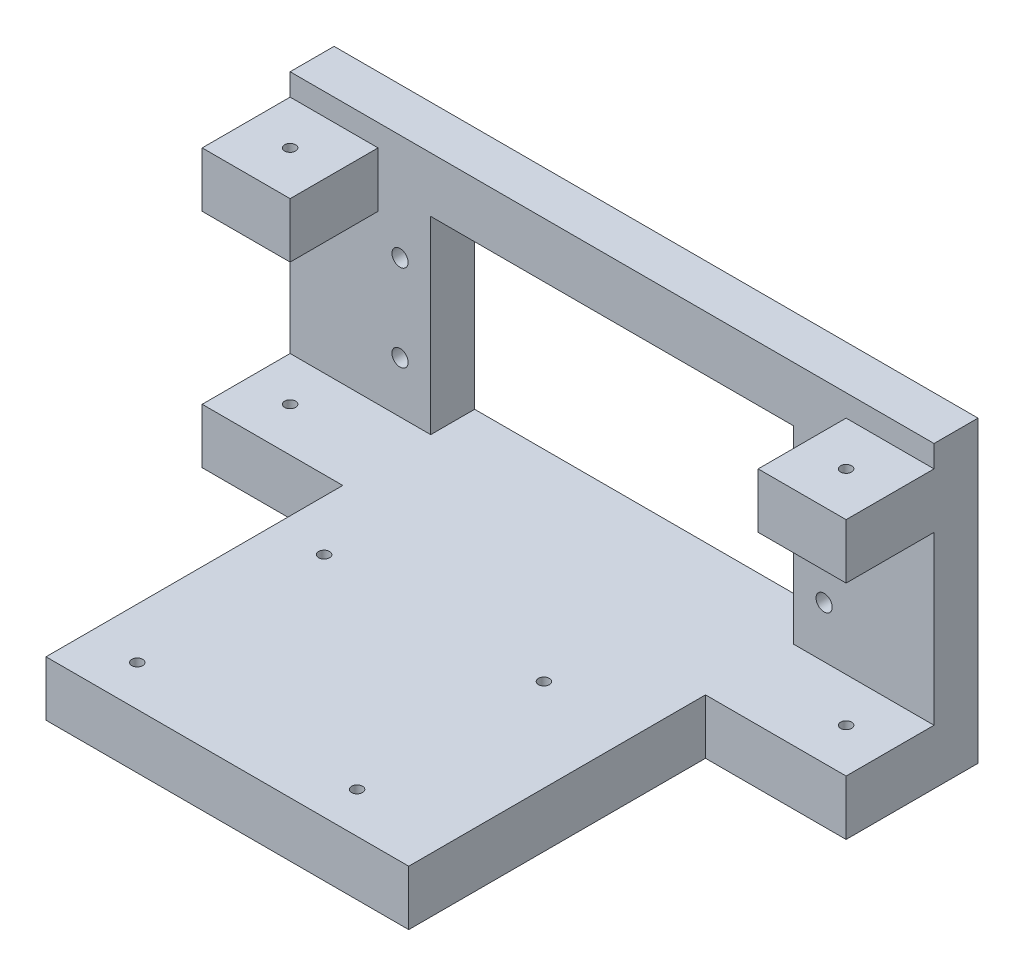
SolidWorks part; units mm, degrees
ref_plane "Front Plane" through (0, 0, 0) normal (0, 0, 1) x (1, 0, 0)
ref_plane "Top Plane" through (0, 0, 0) normal (0, 1, 0) x (1, 0, 0)
ref_plane "Right Plane" through (0, 0, 0) normal (1, 0, 0) x (0, 0, -1)
sketch "Sketch1" plane through (0, 0, 0) normal (0, 0, 1) x (1, 0, 0)
  line L1 (0, 0) -> (54.61, 0)
  line L2 (0, 0) -> (0, 47.244)
  line L3 (0, 47.244) -> (54.61, 47.244)
  line L4 (54.61, 0) -> (54.61, 47.244)
  line L5 (6.35, 12.7) -> (48.26, 12.7)
  line L6 (6.35, 12.7) -> (6.35, 34.544)
  line L7 (6.35, 34.544) -> (48.26, 34.544)
  line L8 (48.26, 12.7) -> (48.26, 34.544)
  dimension "D1" = 41.91
  dimension "D2" = 21.844
  dimension "D3" = 6.35
  dimension "D4" = 6.35
  dimension "D5" = 12.7
  dimension "D6" = 12.7
extrude "Boss-Extrude1" add sketch "Sketch1" along normal blind 5.08
sketch "Sketch2" plane through (0, 0, 5.08) normal (0, 0, 1) x (1, 0, 0)
  line L0 (0, 23.622) -> (54.61, 23.622) construction
  line L1 (2.8054, 28.622) -> (51.8046, 28.622) construction
  line L2 (2.8054, 28.622) -> (2.8054, 18.622) construction
  line L3 (2.8054, 18.622) -> (51.8046, 18.622) construction
  line L4 (51.8046, 28.622) -> (51.8046, 18.622) construction
  line L5 (0, 47.244) -> (0, 0) construction
  line L6 (54.61, 0) -> (54.61, 47.244) construction
  line L7 (2.8054, 23.622) -> (51.8046, 23.622) construction
  line L8 (27.305, 28.622) -> (27.305, 18.622) construction
  line L9 (27.305, 47.244) -> (27.305, 0) construction
  line L10 (54.61, 47.244) -> (0, 47.244) construction
  line L11 (0, 0) -> (54.61, 0) construction
  line L12 (25.1752, 42.164) -> (29.4348, 42.164) construction
  line L13 (29.4348, 42.164) -> (29.4348, 5.08) construction
  line L14 (29.4348, 5.08) -> (25.1752, 5.08) construction
  line L15 (25.1752, 5.08) -> (25.1752, 42.164) construction
  line L16 (48.26, 34.544) -> (6.35, 34.544) construction
  line L17 (6.35, 12.7) -> (48.26, 12.7) construction
  circle A0 centre (2.8054, 28.622) radius 0.936
  circle A1 centre (2.8054, 18.622) radius 0.936
  circle A2 centre (51.8046, 28.622) radius 0.936
  circle A3 centre (51.8046, 18.622) radius 0.936
  circle A4 centre (25.1752, 5.08) radius 0.635 construction
  circle A5 centre (29.4348, 5.08) radius 0.635 construction
  circle A6 centre (29.4348, 42.164) radius 0.635 construction
  circle A7 centre (25.1752, 42.164) radius 0.635 construction
  point P16 (2.8054, 27.686)
  point P17 (2.8054, 19.558)
  dimension "D2" = 8.128
  dimension "D4" = 1.872
  dimension "D5" = 1.27
  dimension "D1" = 10
  dimension "D3" = 48.9991
  dimension "D6" = 4.2596
  dimension "D7" = 2.1298
  dimension "D8" = 7.62
  dimension "D9" = 7.62
  dimension "D10" = 37.084
extrude "Cut-Extrude1" cut sketch "Sketch2" against normal through all
sketch "Sketch10" plane through (0, 0, 5.08) normal (0, 0, 1) x (1, 0, 0)
  line L0 (0, 47.244) -> (0, 80.7756)
  line L1 (0, 80.7756) -> (-31.1018, 80.7756)
  line L2 (0, 47.244) -> (0, 0)
  line L3 (-31.1018, 80.7756) -> (-31.1018, -10.4159)
  line L4 (-31.1018, -10.4159) -> (0, -10.4159)
  line L5 (0, 23.622) -> (54.61, 23.622) construction
  line L6 (54.61, 0) -> (54.61, 47.244) construction
  line L7 (54.61, 23.622) -> (62.23, 23.622) construction
  line L8 (62.23, 23.622) -> (66.4896, 23.622)
  line L9 (-13.8825, 79.8399) -> (-11.43, 79.8399)
  line L10 (-13.8825, 79.8399) -> (-13.8825, 3.6399)
  line L11 (-13.8825, 3.6399) -> (-11.43, 3.6399)
  line L12 (-11.43, 79.8399) -> (-11.43, 3.6399)
  line L13 (0, -10.4159) -> (0, 47.244)
  line L14 (69.0296, 23.622) -> (66.4896, 23.622) construction
  line L15 (0, 47.244) -> (0, 0) construction
  line L16 (64.3598, 25.7518) -> (64.3598, 21.4922) construction
  line L17 (54.61, 33.3718) -> (69.0296, 33.3718)
  line L18 (54.61, 33.3718) -> (54.61, 13.8722)
  line L19 (54.61, 13.8722) -> (69.0296, 13.8722)
  line L20 (69.0296, 33.3718) -> (69.0296, 13.8722)
  line L21 (0, 0) -> (54.61, 0) construction
  line L23 (54.61, 13.1354) -> (54.5843, 13.1354)
  circle A0 centre (-6.7996, 44.704) radius 0.635
  circle A1 centre (-2.54, 44.704) radius 0.635
  circle A2 centre (62.23, 23.622) radius 0.635 construction
  circle A3 centre (66.4896, 23.622) radius 0.635 construction
  circle A4 centre (64.3598, 25.7518) radius 0.635
  circle A5 centre (64.3598, 21.4922) radius 0.635
  point P27 (64.3598, 23.622)
  dimension "D1" = 1.27
  dimension "D10" = 13.8825
  dimension "D11" = 31.1018
  dimension "D2" = 4.2596
  dimension "D3" = 7.62
  dimension "D4" = 2.54
  dimension "D5" = 7.62
  dimension "D6" = 76.2
  dimension "D7" = 2.54
  dimension "D8" = 11.43
  dimension "D9" = 54.5843
  dimension "D12" = 3.6399
  dimension "D13" = 13.1354
  dimension "D14" = 44.704
  dimension "D15" = 80.7756
  dimension "D16" = 10.4159
  dimension "D17" = 4.2596
extrude "Boss-Extrude4" add sketch "Sketch10" against normal up to surface (5.08 mm away)
sketch "Sketch11" plane through (0, 0, 5.08) normal (0, 0, 1) x (1, 0, 0)
  line L0 (0, 47.244) -> (-5.842, 47.244)
  line L1 (-5.842, 47.244) -> (-5.842, 64.262)
  line L2 (-5.842, 64.262) -> (-15.748, 64.262)
  line L3 (-15.748, 64.262) -> (-15.748, -17.018)
  line L4 (-15.748, -17.018) -> (-4.572, -17.018)
  line L5 (-4.572, -17.018) -> (-4.572, 0)
  line L6 (-4.572, 0) -> (0, 0)
  line L7 (0, 0) -> (0, 47.244)
  line L11 (-9.144, 61.722) -> (-5.842, 61.722) construction
  line L12 (-12.446, 61.722) -> (-9.144, 61.722)
  line L13 (-12.446, 61.722) -> (-12.446, -14.478)
  line L14 (-12.446, -14.478) -> (-9.144, -14.478)
  line L15 (-9.144, 61.722) -> (-9.144, -14.478)
  line L16 (-12.446, 61.722) -> (-15.748, 61.722) construction
  line L17 (-12.446, 61.722) -> (-12.446, 64.262) construction
  line L18 (-12.446, -14.478) -> (-12.446, -17.018) construction
  line L19 (0, 47.244) -> (0, 0) construction
  line L20 (0, 0) -> (54.61, 0) construction
  circle A0 centre (64.3598, 25.7518) radius 0.635 construction
  circle A1 centre (64.3598, 21.4922) radius 0.635 construction
  circle A2 centre (64.3598, 25.7518) radius 0.635 construction
  circle A3 centre (64.3598, 21.4922) radius 0.635 construction
  circle A4 centre (-4.572, 21.4922) radius 0.635
  circle A5 centre (-4.572, 25.7518) radius 0.635
  dimension "D10" = 1.27
  dimension "D1" = 76.2
  dimension "D2" = 4.572
  dimension "D3" = 4.572
  dimension "D4" = 3.302
  dimension "D5" = 3.302
  dimension "D6" = 81.28
  dimension "D7" = 15.748
  dimension "D8" = 4.572
  dimension "D9" = 0
  dimension "D11" = 4.2596
  dimension "D12" = 4.572
  dimension "D13" = 21.4922
extrude "Boss-Extrude5" add sketch "Sketch11" against normal up to surface (5.08 mm away) up to face at (52.7406, 18.622, 0)
sketch "Sketch12" plane through (0, 0, 5.08) normal (0, 0, 1) x (1, 0, 0)
  line L0 (54.61, 33.3718) -> (54.61, 47.244) construction
  line L1 (-5.842, 47.244) -> (54.61, 47.244)
  line L2 (-5.842, 47.244) -> (-5.842, 40.894)
  line L3 (-5.842, 40.894) -> (54.61, 40.894)
  line L4 (54.61, 47.244) -> (54.61, 40.894)
  line L5 (54.61, 0) -> (54.61, 13.8722) construction
  line L6 (-4.572, 0) -> (54.61, 0)
  line L7 (-4.572, 0) -> (-4.572, 6.35)
  line L8 (-4.572, 6.35) -> (54.61, 6.35)
  line L9 (54.61, 0) -> (54.61, 6.35)
  line L10 (6.35, 12.7) -> (48.26, 12.7) construction
  line L11 (48.26, 34.544) -> (6.35, 34.544) construction
  line L12 (48.26, 12.7) -> (48.26, 34.544) construction
  line L13 (48.26, 12.7) -> (48.26, 34.544) construction
  dimension "D1" = 6.35
  dimension "D2" = 6.35
  dimension "D3" = 6.35
extrude "Cut-Extrude2" cut sketch "Sketch12" against normal through all
sketch "Sketch13" plane through (0, 0, 0) normal (0, 0, -1) x (-1, 0, 0)
  line L0 (15.748, 64.262) -> (15.748, -17.018) construction
  line L1 (7.1554, 62.8847) -> (14.175, 62.8847)
  line L2 (7.1554, 62.8847) -> (7.1554, -16.1087)
  line L3 (7.1554, -16.1087) -> (14.175, -16.1087)
  line L4 (14.175, 62.8847) -> (14.175, -16.1087)
  line L5 (9.144, 61.722) -> (12.446, 61.722) construction
  line L6 (12.446, -14.478) -> (9.144, -14.478) construction
  dimension "D1" = 7.0196
  dimension "D2" = 1.573
  dimension "D3" = 1.1627
  dimension "D4" = 1.6307
extrude "Boss-Extrude6" add sketch "Sketch13" against normal offset from surface (4.826 mm away) 0.254 up to face at (52.7406, 18.622, 5.08)
fillet "Fillet1" radius 2.54 12 edges at (69.0296, 13.8722, 2.54) (54.61, 6.35, 2.54) (-4.572, 6.35, 2.54) (-4.572, -17.018, 2.54) (-15.748, -17.018, 2.54) (-15.748, 64.262, 2.54) (-5.842, 64.262, 2.54) (-5.842, 40.894, 2.54) (54.61, 40.894, 2.54) (69.0296, 33.3718, 2.54)
sketch "Sketch14" plane through (0, 0, 5.08) normal (0, 0, 1) x (1, 0, 0)
  line L0 (2.8054, 28.622) -> (2.8054, 40.894) construction
  line L1 (-3.302, 40.894) -> (52.07, 40.894) construction
  line L2 (2.8054, 40.894) -> (-0.8159, 40.894)
  line L3 (-0.8159, 40.894) -> (-0.8159, 6.35)
  line L5 (52.07, 6.35) -> (-2.032, 6.35) construction
  line L6 (-0.8159, 6.35) -> (2.8054, 6.35)
  line L7 (2.8054, 6.35) -> (2.8054, -19.9418)
  line L8 (2.8054, -19.9418) -> (-23.5153, -19.9418)
  line L9 (-23.5153, -19.9418) -> (-23.5153, 65.8265)
  line L10 (-23.5153, 65.8265) -> (2.8054, 65.8265)
  line L11 (2.8054, 65.8265) -> (2.8054, 40.894)
  line L12 (51.8046, 28.622) -> (51.8046, 40.8969) construction
  line L13 (51.8046, 40.8969) -> (51.8046, 65.8265)
  line L14 (51.8046, 65.8265) -> (74.4862, 65.8265)
  line L15 (74.4862, 65.8265) -> (74.4862, -19.9418)
  line L16 (74.4862, -19.9418) -> (51.8046, -19.9418)
  line L17 (51.8046, -19.9418) -> (52.07, 6.35)
  line L18 (52.07, 6.35) -> (54.61, 8.89)
  line L19 (54.61, 8.89) -> (54.61, 38.354)
  line L20 (54.61, 38.354) -> (51.8046, 40.8969)
  line L21 (-15.748, 61.722) -> (-15.748, -14.478) construction
  line L22 (-8.382, 64.262) -> (-13.208, 64.262) construction
  dimension "D1" = 14.9321
  dimension "D2" = 90.2342
  dimension "D3" = 7.7673
  dimension "D4" = 1.5645
  dimension "D5" = 23.3651
  dimension "D6" = 84.2038
extrude "Cut-Extrude3" cut sketch "Sketch14" against normal through all
sketch "Sketch15" plane through (0, 0, 5.08) normal (0, 0, 1) x (1, 0, 0)
  line L0 (-0.8159, 40.894) -> (-9.8946, 40.894)
  line L1 (-9.8946, 40.894) -> (-9.8946, 6.35)
  line L2 (-9.8946, 6.35) -> (-0.8159, 6.35)
  line L3 (-0.8159, 6.35) -> (-0.8159, 40.894) construction
  line L4 (-0.8159, 6.35) -> (-0.8159, 40.894)
  line L5 (51.8077, 40.894) -> (54.61, 38.354)
  line L6 (54.61, 38.354) -> (54.61, 8.89)
  line L7 (54.61, 8.89) -> (54.61, 38.354) construction
  line L8 (54.61, 8.89) -> (52.07, 6.35)
  line L9 (52.07, 6.35) -> (64.5046, 6.35)
  line L10 (64.5046, 6.35) -> (64.5046, 40.894)
  line L11 (64.5046, 40.894) -> (51.8077, 40.894)
  circle A0 centre (2.8054, 28.622) radius 0.936 construction
  circle A1 centre (2.8054, 28.622) radius 0.936 construction
  circle A2 centre (51.8046, 28.622) radius 0.936 construction
  circle A3 centre (51.8046, 28.622) radius 0.936 construction
  dimension "D1" = 12.7
  dimension "D2" = 3.6214
  dimension "D3" = 12.7
extrude "Boss-Extrude7" add sketch "Sketch15" against normal up to surface (5.08 mm away) up to face at (35.2443, 21.1667, 0)
sketch "Sketch16" plane through (0, 0, 5.08) normal (0, 0, 1) x (1, 0, 0)
  line L0 (-9.8946, 40.894) -> (64.5046, 40.894) construction
  line L3 (48.26, 23.622) -> (64.5046, 23.622) construction
  line L4 (48.26, 12.7) -> (48.26, 34.544) construction
  line L5 (64.5046, 6.35) -> (64.5046, 40.894) construction
  line L6 (0.2654, 38.354) -> (-9.8946, 38.354)
  line L7 (0.2654, 38.354) -> (0.2654, 32.004)
  line L8 (-9.8946, 38.354) -> (-9.8946, 32.004)
  line L9 (0.2654, 32.004) -> (-9.8946, 32.004)
  line L10 (0.2654, 38.354) -> (-9.8946, 32.004) construction
  line L11 (-9.8946, 38.354) -> (0.2654, 32.004) construction
  line L12 (27.305, 34.544) -> (27.305, 12.7) construction
  line L13 (48.26, 34.544) -> (6.35, 34.544) construction
  line L14 (6.35, 12.7) -> (48.26, 12.7) construction
  line L15 (54.3446, 38.354) -> (54.3446, 32.004)
  line L16 (54.3446, 32.004) -> (64.5046, 32.004)
  line L17 (64.5046, 38.354) -> (64.5046, 32.004)
  line L18 (54.3446, 38.354) -> (64.5046, 38.354)
  point P12 (-9.8946, 35.179)
  point P13 (-4.8146, 35.179)
  dimension "D1" = 6.35
  dimension "D2" = 10.16
  dimension "D3" = 2.54
extrude "Boss-Extrude8" add sketch "Sketch16" along normal blind 10.16
sketch "Sketch19" plane through (0, 0, 5.08) normal (0, 0, 1) x (1, 0, 0)
  line L0 (64.5046, 6.35) -> (-9.8946, 6.35) construction
  line L1 (6.35, 12.7) -> (48.26, 12.7)
  line L2 (6.35, 12.7) -> (6.35, 6.35)
  line L3 (6.35, 6.35) -> (48.26, 6.35)
  line L4 (48.26, 12.7) -> (48.26, 6.35)
  line L5 (48.26, 12.7) -> (48.26, 34.544) construction
extrude "Boss-Extrude10" add sketch "Sketch19" along normal blind 44.45
sketch "Sketch20" plane through (0, 6.35, 0) normal (0, -1, 0) x (-1, 0, 0)
  line L1 (-6.35, -5.08) -> (9.8946, -5.08)
  line L2 (-6.35, -5.08) -> (-6.35, -15.24)
  line L3 (-6.35, -15.24) -> (9.8946, -15.24)
  line L4 (9.8946, -5.08) -> (9.8946, -15.24)
  line L5 (-48.26, -5.08) -> (-64.5046, -5.08)
  line L6 (-48.26, -5.08) -> (-48.26, -15.24)
  line L7 (-48.26, -15.24) -> (-64.5046, -15.24)
  line L8 (-64.5046, -5.08) -> (-64.5046, -15.24)
extrude "Boss-Extrude11" add sketch "Sketch20" against normal up to surface (6.35 mm away) up to face at (27.305, 12.7, 18.2033)
sketch "Sketch17" plane through (0, 38.354, 0) normal (0, 1, 0) x (1, 0, 0)
  line L0 (0.2654, -15.24) -> (-9.8946, -5.08) construction
  line L1 (27.305, -5.08) -> (27.305, -12.7) construction
  line L2 (-9.8946, -5.08) -> (64.5046, -5.08) construction
  circle A0 centre (-4.8146, -10.16) radius 0.635
  circle A1 centre (59.4246, -10.16) radius 0.635
  dimension "D1" = 1.27
extrude "Cut-Extrude4" cut sketch "Sketch17" against normal through all
sketch "Sketch21" plane through (0, 6.35, 0) normal (0, -1, 0) x (1, 0, 0)
  line L0 (37.592, 23.241) -> (37.592, 44.831) construction
  line L1 (37.592, 44.831) -> (12.192, 44.831) construction
  line L2 (12.192, 44.831) -> (12.192, 23.241) construction
  line L3 (12.192, 23.241) -> (37.592, 23.241) construction
  circle A0 centre (37.592, 23.241) radius 0.635
  circle A1 centre (37.592, 44.831) radius 0.635
  circle A2 centre (12.192, 44.831) radius 0.635
  circle A3 centre (12.192, 23.241) radius 0.635
  dimension "D1" = 1.27
extrude "Cut-Extrude5" cut sketch "Sketch21" against normal through all
equation "\"D7@Sketch2\"=\"D6@Sketch2\"/2"
equation "\"D8@Sketch11\" = \"D2@Sketch11\""
equation "\"D1@Sketch12\"=\"D3@Sketch12\""
equation "\"D2@Sketch12\"= \"D1@Sketch12\""
equation "\"D3@Sketch11\"= \"D2@Sketch11\""
